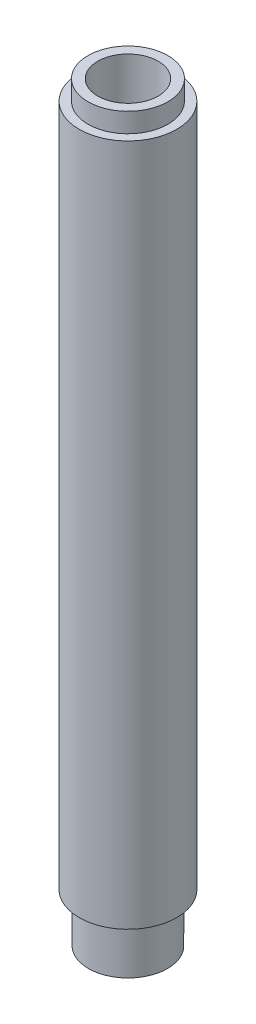
SolidWorks part; units mm, degrees
ref_plane "Front Plane" through (0, 0, 0) normal (0, 0, 1) x (1, 0, 0)
ref_plane "Top Plane" through (0, 0, 0) normal (0, 1, 0) x (1, 0, 0)
ref_plane "Right Plane" through (0, 0, 0) normal (1, 0, 0) x (0, 0, -1)
sketch "Sketch1" plane through (0, 0, 0) normal (0, 1, 0) x (1, 0, 0)
  circle A0 centre (0, 0) radius 12.7
  dimension "D1" = 25.4
extrude "Boss-Extrude1" add sketch "Sketch1" along normal blind 177.8
sketch "Sketch4" plane through (0, 177.8, 0) normal (0, 1, 0) x (1, 0, 0)
  circle A0 centre (0, 0) radius 12.7 construction
  circle A3 centre (0, 0) radius 10.414
  dimension "D1" = 20.828
  dimension "D2" = 2.286
extrude "Boss-Extrude2" add sketch "Sketch4" along normal blind 5.08
sketch "Sketch5" plane through (0, 182.88, 0) normal (0, 1, 0) x (1, 0, 0)
  circle A0 centre (0, 0) radius 10.414 construction
  circle A1 centre (0, 0) radius 10.414 construction
  circle A2 centre (0, 0) radius 7.874
  dimension "D1" = 2.54
extrude "Cut-Extrude1" cut sketch "Sketch5" against normal through all
sketch "Sketch6" plane through (0, 0, 0) normal (0, -1, 0) x (1, 0, 0)
  circle A0 centre (0, 0) radius 10.287
  circle A1 centre (0, 0) radius 7.874 construction
  circle A2 centre (0, 0) radius 7.874
  dimension "D1" = 20.574
extrude "Boss-Extrude3" add sketch "Sketch6" along normal blind 12.7
